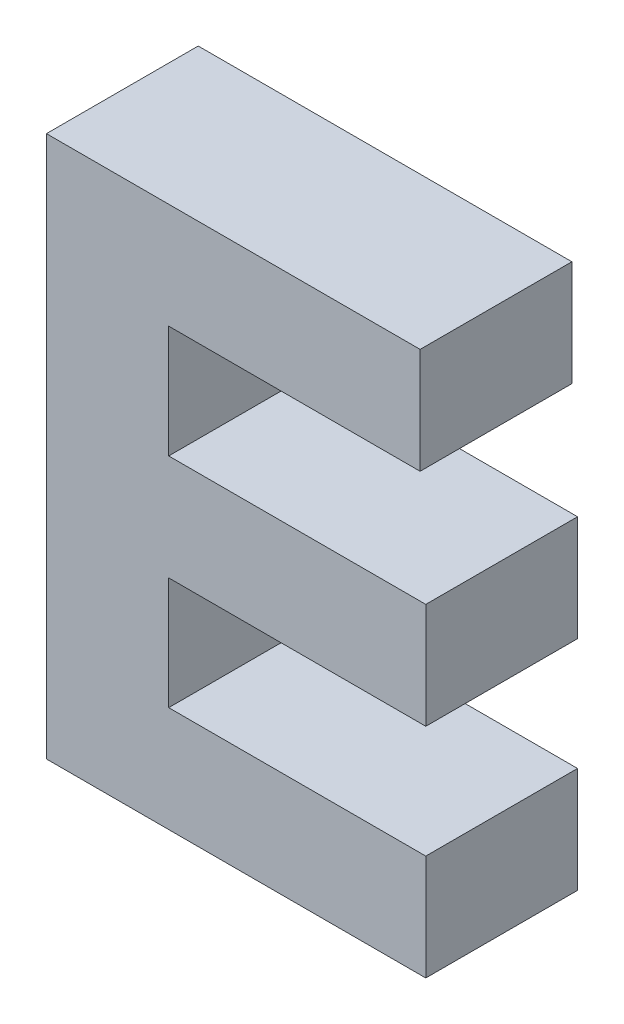
SolidWorks part; units mm, degrees
ref_plane "Front Plane" through (0, 0, 0) normal (0, 0, 1) x (1, 0, 0)
ref_plane "Top Plane" through (0, 0, 0) normal (0, 1, 0) x (1, 0, 0)
ref_plane "Right Plane" through (0, 0, 0) normal (1, 0, 0) x (0, 0, -1)
sketch "Sketch1" plane through (0, 0, 0) normal (0, 0, 1) x (1, 0, 0)
  line L0 (-102.3875, 59.8298) -> (-102.3875, -65.0632)
  line L1 (-102.3875, -65.0632) -> (-14.9133, -65.0632)
  line L2 (-102.3875, 59.8298) -> (-16.2157, 59.8298)
  line L3 (-16.2157, 59.8298) -> (-16.2157, 35.4803)
  line L4 (-16.2157, 35.4803) -> (-75.4957, 35.4803)
  line L5 (-75.4957, 35.4803) -> (-74.1933, 35.4803)
  line L6 (-74.1933, 35.4803) -> (-74.1933, 9.5568)
  line L7 (-74.1933, 9.5568) -> (-14.9101, 9.5568)
  line L8 (-14.9101, 9.5568) -> (-14.9101, -14.7932)
  line L9 (-14.9101, -14.7932) -> (-74.1933, -14.7932)
  line L10 (-74.1933, -14.7932) -> (-74.1933, -40.7132)
  line L11 (-74.1933, -40.7132) -> (-14.9133, -40.7132)
  line L12 (-14.9133, -40.7132) -> (-14.9133, -65.0632)
  line L13 (-14.9133, -65.0632) -> (-15.3003, -65.8371)
  dimension "D1" = 59.28
  dimension "D2" = 59.2833
  dimension "D3" = 86.1718
  dimension "D4" = 59.28
  dimension "D5" = 25.9235
  dimension "D6" = 25.92
  dimension "D7" = 24.3496
  dimension "D8" = 24.35
  dimension "D9" = 24.35
extrude "Boss-Extrude1" add sketch "Sketch1" along normal blind 35
sketch "Sketch2" plane through (0, -65.0632, 0) normal (0, -1, 0) x (1, 0, 0)
  circle A0 centre (-86.6286, 15.9919) radius 9.963
  circle A1 centre (-55.3001, 15.9919) radius 9.963
extrude "Cut-Extrude1" cut sketch "Sketch2" against normal blind 10
